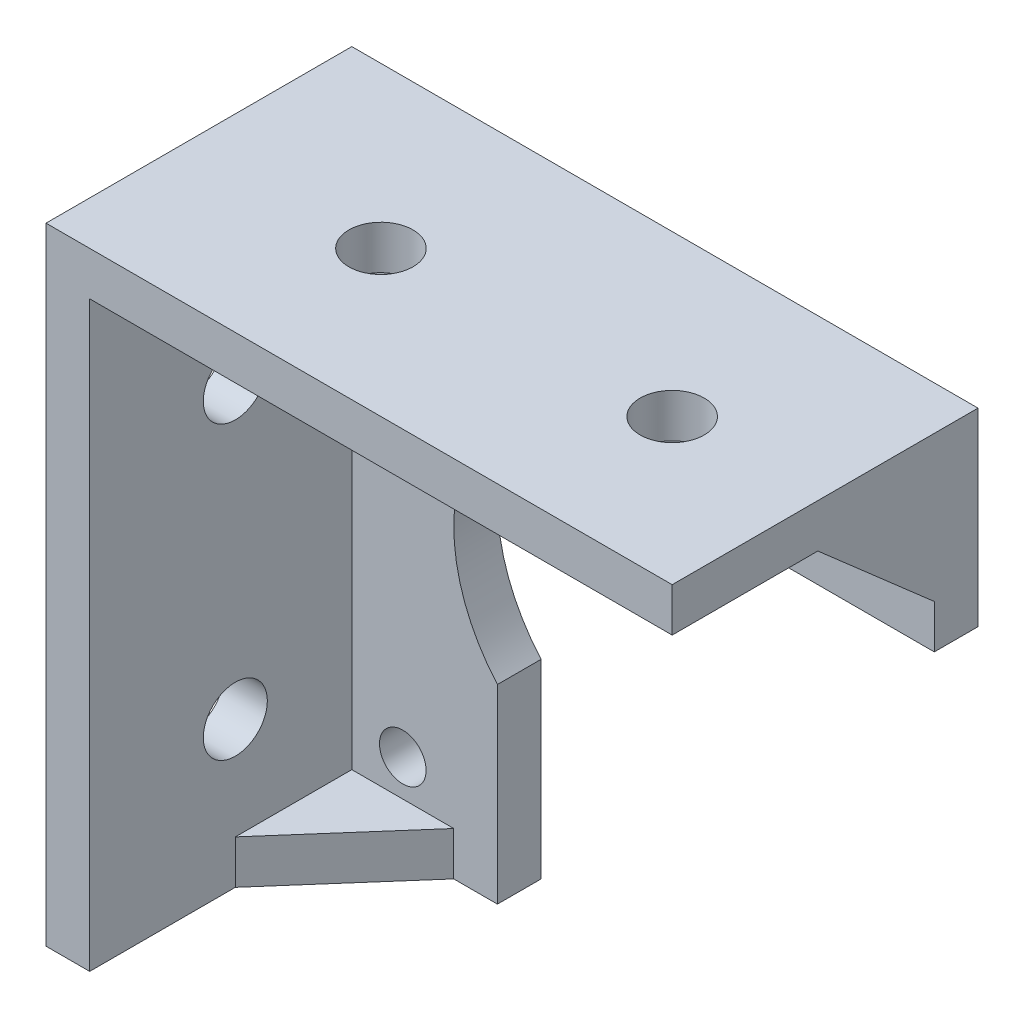
SolidWorks part; units mm, degrees
material "ABS"
ref_plane "Front Plane" through (0, 0, 0) normal (0, 0, 1) x (1, 0, 0)
ref_plane "Top Plane" through (0, 0, 0) normal (0, 1, 0) x (1, 0, 0)
ref_plane "Right Plane" through (0, 0, 0) normal (1, 0, 0) x (0, 0, -1)
sketch "Sketch1" plane through (0, 0, 0) normal (0, 0, 1) x (1, 0, 0)
  line L0 (0, -43) -> (0, 0)
  line L1 (0, 0) -> (43, 0)
  line L2 (43, 0) -> (43, -13)
  line L3 (19, -13) -> (13, -19)
  line L4 (13, -43) -> (0, -43)
  line L5 (13, -43) -> (13, -19)
  line L6 (43, -13) -> (19, -13)
  dimension "D1" = 43
  dimension "D2" = 13
  dimension "D3" = 13
  dimension "D4" = 24
  dimension "D5" = 45
extrude "Boss-Extrude1" add sketch "Sketch1" along normal blind 3
sketch "Sketch2" plane through (0, 0, 3) normal (0, 0, 1) x (1, 0, 0)
  line L0 (0, -43) -> (3, -43)
  line L1 (0, -43) -> (13, -43) construction
  line L2 (3, -43) -> (3, -3)
  line L3 (3, -3) -> (43, -3)
  line L4 (43, -13) -> (43, 0) construction
  line L5 (43, -3) -> (43, 0)
  line L6 (43, 0) -> (0, 0)
  line L7 (0, 0) -> (0, -43)
  dimension "D1" = 3
extrude "Boss-Extrude2" add sketch "Sketch2" along normal blind 18
sketch "Sketch3" plane through (0, 0, 3) normal (0, 0, 1) x (1, 0, 0)
  line L0 (0, 0) -> (0, -43) construction
  line L1 (43, 0) -> (0, 0) construction
  circle A0 centre (22, -22) radius 12
  dimension "D1" = 24
  dimension "D2" = 22
  dimension "D3" = 22
extrude "Cut-Extrude1" cut sketch "Sketch3" against normal through all
sketch "Sketch4" plane through (0, 0, 3) normal (0, 0, 1) x (1, 0, 0)
  line L0 (0, 0) -> (0, -43) construction
  line L1 (43, 0) -> (0, 0) construction
  circle A0 centre (6.5, -6.5) radius 1.6
  circle A1 centre (37.5, -6.5) radius 1.6
  circle A2 centre (6.5, -37.5) radius 1.6
  dimension "D1" = 31
  dimension "D2" = 31
  dimension "D3" = 3.2
  dimension "D4" = 6.5
  dimension "D5" = 6.5
extrude "Cut-Extrude2" cut sketch "Sketch4" against normal through all
sketch "Sketch5" plane through (43, 0, 0) normal (1, 0, 0) x (0, 0, -1)
  line L0 (-3, -10) -> (-11, -3)
  line L1 (-3, -13) -> (-3, -3) construction
  line L2 (-21, -3) -> (-3, -3) construction
  line L3 (-11, -3) -> (-3, -3)
  line L4 (-3, -3) -> (-3, -10)
  line L5 (-3, -13) -> (0, -13) construction
  line L6 (-21, -3) -> (-21, 0) construction
  dimension "D1" = 3
  dimension "D2" = 10
extrude "Boss-Extrude3" add sketch "Sketch5" against normal blind 2
sketch "Sketch6" plane through (0, -43, 0) normal (0, -1, 0) x (1, 0, 0)
  line L0 (3, 11) -> (10, 3)
  line L1 (3, 21) -> (3, 3) construction
  line L2 (3, 3) -> (13, 3) construction
  line L3 (10, 3) -> (3, 3)
  line L4 (3, 3) -> (3, 11)
  line L5 (0, 21) -> (3, 21) construction
  line L6 (13, 3) -> (13, 0) construction
  dimension "D1" = 10
  dimension "D2" = 3
extrude "Boss-Extrude4" add sketch "Sketch6" against normal blind 3
sketch "Sketch7" plane through (0, -3, 0) normal (0, -1, 0) x (1, 0, 0)
  line L0 (3, 21) -> (43, 21) construction
  line L1 (0, 21) -> (0, 0) construction
  circle A0 centre (13, 11) radius 2.2
  circle A1 centre (33, 11) radius 2.2
  dimension "D1" = 4.4
  dimension "D2" = 10
  dimension "D3" = 20
  dimension "D4" = 13
extrude "Cut-Extrude3" cut sketch "Sketch7" against normal through all
sketch "Sketch8" plane through (3, 0, 0) normal (1, 0, 0) x (0, 0, -1)
  line L0 (-21, -43) -> (-21, -3) construction
  line L1 (-21, 0) -> (0, 0) construction
  circle A0 centre (-11, -33) radius 2.2
  circle A1 centre (-11, -13) radius 2.2
  dimension "D1" = 4.4
  dimension "D2" = 10
  dimension "D3" = 20
  dimension "D4" = 13
extrude "Cut-Extrude4" cut sketch "Sketch8" against normal through all
